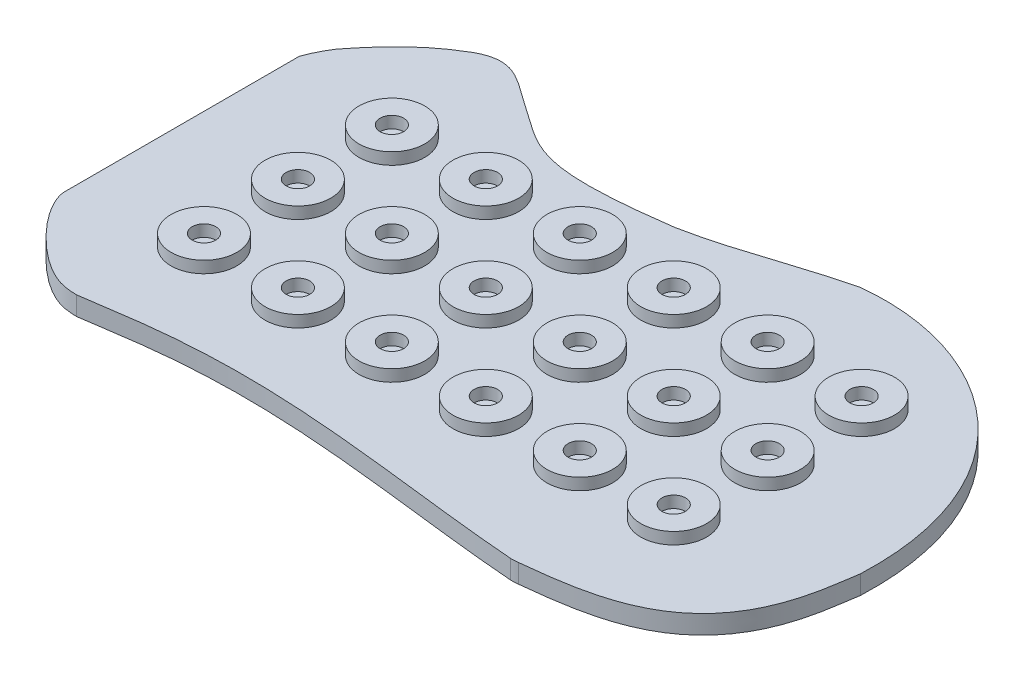
SolidWorks part; units mm, degrees
ref_plane "Front Plane" through (0, 0, 0) normal (0, 0, 1) x (1, 0, 0)
ref_plane "Top Plane" through (0, 0, 0) normal (0, 1, 0) x (1, 0, 0)
ref_plane "Right Plane" through (0, 0, 0) normal (1, 0, 0) x (0, 0, -1)
other "Center of Mass"
sketch "Sketch1" plane through (0, 0, 0) normal (0, 1, 0) x (1, 0, 0)
  line L0 (-78.6109, 24.9032) -> (-78.6109, -25.142)
  line L1 (78.526, -10.9955) -> (-78.6109, -10.9955) construction
  line L2 (-77.6109, 24.7348) -> (-77.6109, -25.142)
  line L3 (78.526, -11.9955) -> (-78.6109, -11.9955)
  arc A0 (37.4157, -46.3273) -> (39.1437, -46.2432) centre (37.8097, -36.6353) ccw
  arc A1 (37.4725, -45.3288) -> (39.0215, -45.2505) centre (37.8097, -36.6353) ccw
  spline S0 degree 3 poles (-77.6109, -25.142) (-77.6103, -25.4) (-77.563, -25.903) (-77.2897, -26.9857) (-76.6417, -28.5306) (-75.4978, -30.4481) (-73.6058, -33.039) (-70.8033, -36.112) (-67.3274, -39.127) (-64.1402, -41.244) (-61.4556, -42.4361) (-59.2812, -42.8778) (-58.0256, -42.9092) (-57.3728, -42.9466) knots 0.000484 0.000484 0.000484 0.000484 0.031521 0.062558 0.124632 0.186706 0.248781 0.372929 0.497077 0.621225 0.745373 0.869521 0.993669 0.993669 0.993669 0.993669
  spline S1 degree 3 poles (-57.3728, -42.9466) (-57.1306, -42.9172) (-56.6559, -42.8572) (-55.6329, -42.7168) (-54.2832, -42.5176) (-52.5297, -42.2482) (-50.0282, -41.8652) (-46.6003, -41.367) (-42.0363, -40.8111) (-37.0514, -40.3559) (-29.8812, -39.9429) (-20.0109, -39.8766) (-6.9377, -40.6174) (4.791, -41.8163) (14.5692, -42.9593) (22.0672, -43.8389) (29.7001, -44.6718) (34.8871, -45.1373) (37.4725, -45.3288) knots 0.000538 0.000538 0.000538 0.000538 0.016152 0.031766 0.062993 0.094221 0.125449 0.187904 0.250359 0.312815 0.37527 0.50018 0.625091 0.750001 0.812457 0.874912 0.937367 0.999822 0.999822 0.999822 0.999822
  spline S2 degree 3 poles (39.0215, -45.2505) (40.5541, -45.0873) (43.6362, -44.7445) (49.6297, -43.8727) (56.6431, -42.2158) (63.7646, -38.9137) (69.3225, -34.2155) (72.596, -29.3087) (74.4639, -25.0567) (75.5267, -21.803) (76.2971, -18.6022) (76.7457, -16.0939) (77.026, -14.2578) (77.207, -12.9947) (77.3723, -11.8407) (77.4763, -11.2132) (77.5311, -10.8821) knots -0.000309 -0.000309 -0.000309 -0.000309 0.063093 0.126495 0.253299 0.380104 0.506908 0.633712 0.697114 0.760516 0.823918 0.88732 0.919021 0.950722 0.982423 1.014124 1.014124 1.014124 1.014124
  spline S3 degree 3 poles (77.5311, -10.8821) (77.5748, -9.7665) (77.6099, -7.5074) (77.4888, -4.2729) (77.2058, -1.1252) (76.6195, 2.9373) (75.5088, 7.7538) (72.9895, 14.9059) (68.5668, 22.78) (61.5957, 30.4634) (53.3357, 36.3146) (44.1583, 40.2648) (34.4498, 42.2506) (27.8575, 42.2059) (24.6064, 41.8434) knots 0.000169 0.000169 0.000169 0.000169 0.031414 0.062658 0.093902 0.125147 0.187635 0.250124 0.375101 0.500079 0.625056 0.750034 0.875011 0.999988 0.999988 0.999988 0.999988
  spline S4 degree 3 poles (24.6064, 41.8434) (19.4417, 40.5996) (11.8686, 38.1019) (1.7069, 34.9414) (-3.4909, 33.6615) (-6.1131, 33.1605) knots 0.000659 0.000659 0.000659 0.000659 0.498067 0.746772 0.995476 0.995476 0.995476 0.995476
  spline S5 degree 3 poles (-6.1131, 33.1605) (-7.1417, 33.0163) (-9.1825, 32.742) (-13.4171, 32.237) (-18.6364, 31.7654) (-24.3553, 31.6023) (-29.2844, 31.96) (-33.4204, 32.9216) (-36.3715, 34.2616) (-38.6497, 35.6481) (-40.393, 36.836) (-41.9608, 37.95) (-43.3176, 38.8994) (-44.0701, 39.4107) (-44.4391, 39.6587) knots -0.000196 -0.000196 -0.000196 -0.000196 0.062587 0.12537 0.250936 0.376501 0.502067 0.627632 0.753198 0.815981 0.878764 0.941546 0.972938 1.004329 1.004329 1.004329 1.004329
  spline S6 degree 3 poles (-44.4391, 39.6587) (-44.6983, 39.8375) (-45.2219, 40.2027) (-46.2044, 40.9033) (-47.345, 41.7292) (-48.5998, 42.6198) (-50.1509, 43.6513) (-51.9146, 44.6189) (-53.8615, 45.2294) (-55.7055, 45.3275) (-57.1648, 45.051) (-58.2486, 44.6839) (-59.0003, 44.3616) (-59.6837, 44.0129) (-60.0375, 43.8061) (-60.2239, 43.694) knots -0.002497 -0.002497 -0.002497 -0.002497 0.029066 0.060629 0.123754 0.18688 0.250006 0.376257 0.502509 0.62876 0.755012 0.818137 0.881263 0.944389 1.007515 1.007515 1.007515 1.007515
  spline S7 degree 3 poles (-78.6109, -25.142) (-78.6097, -25.7822) (-78.3711, -27.0076) (-77.5216, -29.0127) (-76.3076, -31.0396) (-74.3365, -33.7283) (-71.4439, -36.8883) (-67.8634, -39.9802) (-64.5529, -42.1647) (-61.6917, -43.4202) (-59.6968, -43.8088) (-58.2959, -43.9054) (-57.6656, -43.9305) (-57.3419, -43.9502) knots 0.000409 0.000409 0.000409 0.000409 0.062843 0.125276 0.18771 0.250143 0.375011 0.499878 0.624745 0.749612 0.874479 0.936913 0.999346 0.999346 0.999346 0.999346
  spline S8 degree 3 poles (-57.3419, -43.9502) (-57.0965, -43.9206) (-56.6141, -43.8604) (-55.5847, -43.7202) (-54.2292, -43.5208) (-52.4771, -43.2519) (-49.983, -42.8696) (-46.5727, -42.3725) (-42.0367, -41.817) (-37.0824, -41.3612) (-29.9535, -40.9457) (-20.1287, -40.874) (-7.0907, -41.608) (4.6318, -42.8047) (14.4219, -43.9489) (21.9389, -44.8307) (29.5994, -45.6669) (34.8166, -46.135) (37.4157, -46.3273) knots -0.001373 -0.001373 -0.001373 -0.001373 0.014273 0.029919 0.06121 0.092502 0.123794 0.186377 0.24896 0.311543 0.374127 0.499293 0.62446 0.749626 0.81221 0.874793 0.937376 0.99996 0.99996 0.99996 0.99996
  spline S9 degree 3 poles (39.1437, -46.2432) (40.686, -46.0789) (43.7818, -45.7344) (49.848, -44.8507) (56.9964, -43.16) (64.3453, -39.7462) (70.1244, -34.8409) (73.5118, -29.7304) (75.4294, -25.3355) (76.5134, -21.9918) (77.2941, -18.7213) (77.7459, -16.1748) (78.0266, -14.3264) (78.2075, -13.0606) (78.3702, -11.9307) (78.4738, -11.3105) (78.5279, -10.984) knots -0.000086 -0.000086 -0.000086 -0.000086 0.063428 0.126941 0.253967 0.380993 0.50802 0.635046 0.698559 0.762072 0.825585 0.889098 0.920855 0.952612 0.984368 1.016125 1.016125 1.016125 1.016125
  spline S10 degree 3 poles (78.5279, -10.984) (78.5733, -9.8502) (78.6109, -7.5559) (78.4906, -4.2601) (78.2049, -1.0549) (77.6104, 3.0871) (76.4803, 8.0028) (73.9108, 15.31) (69.3901, 23.3646) (62.2582, 31.2245) (53.8088, 37.2052) (44.4261, 41.2372) (34.4991, 43.2588) (27.7571, 43.2053) (24.4331, 42.8302) knots -0.000407 -0.000407 -0.000407 -0.000407 0.03088 0.062166 0.093453 0.12474 0.187314 0.249888 0.375035 0.500183 0.62533 0.750478 0.875625 1.000773 1.000773 1.000773 1.000773
  spline S11 degree 3 poles (24.4331, 42.8302) (21.8301, 42.2051) (16.6685, 40.7402) (6.525, 37.4536) (-1.0744, 35.1413) (-6.2764, 34.1474) knots -0.001281 -0.001281 -0.001281 -0.001281 0.247714 0.49671 0.9947 0.9947 0.9947 0.9947
  spline S12 degree 3 poles (-6.2764, 34.1474) (-7.3001, 34.0039) (-9.3317, 33.7312) (-13.542, 33.2295) (-18.7181, 32.7628) (-24.3556, 32.604) (-29.1564, 32.9561) (-33.1061, 33.8787) (-35.9015, 35.1472) (-38.1022, 36.4854) (-39.8157, 37.6526) (-41.3786, 38.7631) (-42.7458, 39.7198) (-43.5043, 40.2353) (-43.8763, 40.4853) knots 0.000305 0.000305 0.000305 0.000305 0.063048 0.125791 0.251276 0.376761 0.502247 0.627732 0.753218 0.815961 0.878703 0.941446 0.972817 1.004189 1.004189 1.004189 1.004189
  spline S13 degree 3 poles (-43.8763, 40.4853) (-44.1324, 40.662) (-44.6496, 41.0228) (-45.6222, 41.7163) (-46.7618, 42.5415) (-48.0307, 43.4423) (-49.6264, 44.5037) (-51.4979, 45.535) (-53.6685, 46.2221) (-55.7733, 46.3353) (-57.4106, 46.0235) (-58.6015, 45.6208) (-59.4227, 45.2686) (-60.0246, 44.9622) (-60.4597, 44.7184) (-60.6399, 44.6107) (-60.7341, 44.5541) knots -0.002294 -0.002294 -0.002294 -0.002294 0.029245 0.060783 0.12386 0.186936 0.250013 0.376167 0.50232 0.628473 0.754627 0.817704 0.88078 0.943857 0.975396 1.006934 1.006934 1.006934 1.006934
  spline S14 degree 3 poles (-60.7341, 44.5541) (-61.1687, 44.2998) (-62.0358, 43.7712) (-63.676, 42.6889) (-66.3643, 40.7074) (-69.6969, 37.7112) (-72.4782, 34.663) (-74.193, 32.5981) (-75.1195, 31.4458) (-75.5587, 30.8903) (-75.7803, 30.6092) knots 0.000427 0.000427 0.000427 0.000427 0.063268 0.126109 0.251792 0.503158 0.754524 0.880206 0.943048 1.005889 1.005889 1.005889 1.005889
  spline S15 degree 3 poles (-60.2239, 43.694) (-60.6474, 43.4463) (-61.4924, 42.9314) (-63.0906, 41.8773) (-65.7124, 39.9465) (-68.9709, 37.0199) (-71.6981, 34.0358) (-73.6437, 31.6948) (-74.5236, 30.5881) (-74.9696, 30.0223) knots 0.000174 0.000174 0.000174 0.000174 0.062881 0.125589 0.251004 0.501833 0.752662 0.878077 1.003492 1.003492 1.003492 1.003492
  spline S16 degree 3 poles (-74.9696, 30.0223) (-75.5195, 29.1919) (-76.5302, 27.448) (-77.2874, 25.6577) (-77.6109, 24.7348) knots 0.499549 0.499549 0.499549 0.499549 0.499766 0.499983 0.499983 0.499983 0.499983
  spline S17 degree 3 poles (-75.7803, 30.6092) (-76.3738, 29.7162) (-77.4602, 27.8403) (-78.2688, 25.9015) (-78.6109, 24.9032) knots 0.499546 0.499546 0.499546 0.499546 0.49977 0.499995 0.499995 0.499995 0.499995
  point P0 (0.0094, -10.9955)
extrude "Boss-Extrude2" add sketch "Sketch1" along normal blind 4 contours L1 S2 S3 S4 S5 S6 S15 S16 L2 | S2 L1 L2 L3 | A1 S2 L3 L2 S0 S1
ref_plane "Plane1" through (0, 0, -24.7348) normal (0, 0, -1) x (0, -1, 0)
sketch "Sketch2" plane through (0, 4, 0) normal (0, 1, 0) x (1, 0, 0)
  circle A0 centre (-52.6013, 19.445) radius 7
  dimension "D1" = 14
extrude "Boss-Extrude3" add sketch "Sketch2" along normal blind 2.5
sketch "Sketch4" plane through (0, 6.5, 0) normal (0, 1, 0) x (1, 0, 0)
  circle A0 centre (-52.6013, 19.445) radius 2.5
extrude "Cut-Extrude1" cut sketch "Sketch4" against normal blind 2.5
pattern_linear "LPattern1" count 3 spacing 20 along (0, 0, 1) count 6 spacing 20 along (1, 0, 0) of "Cut-Extrude1", "Boss-Extrude3"
other "Center of Mass Reference Point2"
